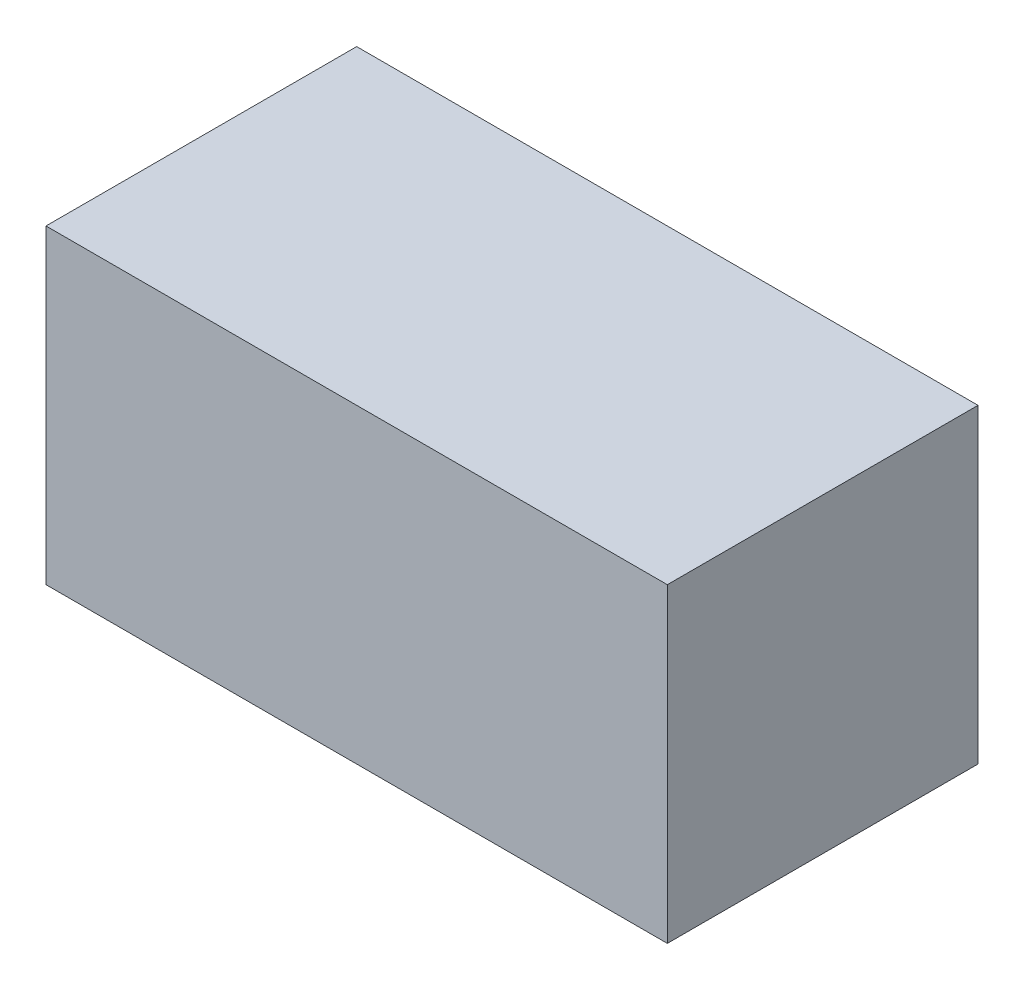
SolidWorks part; units mm, degrees
ref_plane "前视基准面" through (0, 0, 0) normal (0, 0, 1) x (1, 0, 0)
ref_plane "上视基准面" through (0, 0, 0) normal (0, 1, 0) x (1, 0, 0)
ref_plane "右视基准面" through (0, 0, 0) normal (1, 0, 0) x (0, 0, -1)
other "Configuration Table"
sketch "草图1" plane through (0, 0, 0) normal (0, 1, 0) x (1, 0, 0)
  line L1 (0, 0) -> (100, 0)
  line L2 (0, 0) -> (0, 50)
  line L3 (0, 50) -> (100, 50)
  line L4 (100, 0) -> (100, 50)
extrude "凸台-拉伸1" add sketch "草图1" along normal blind 50
